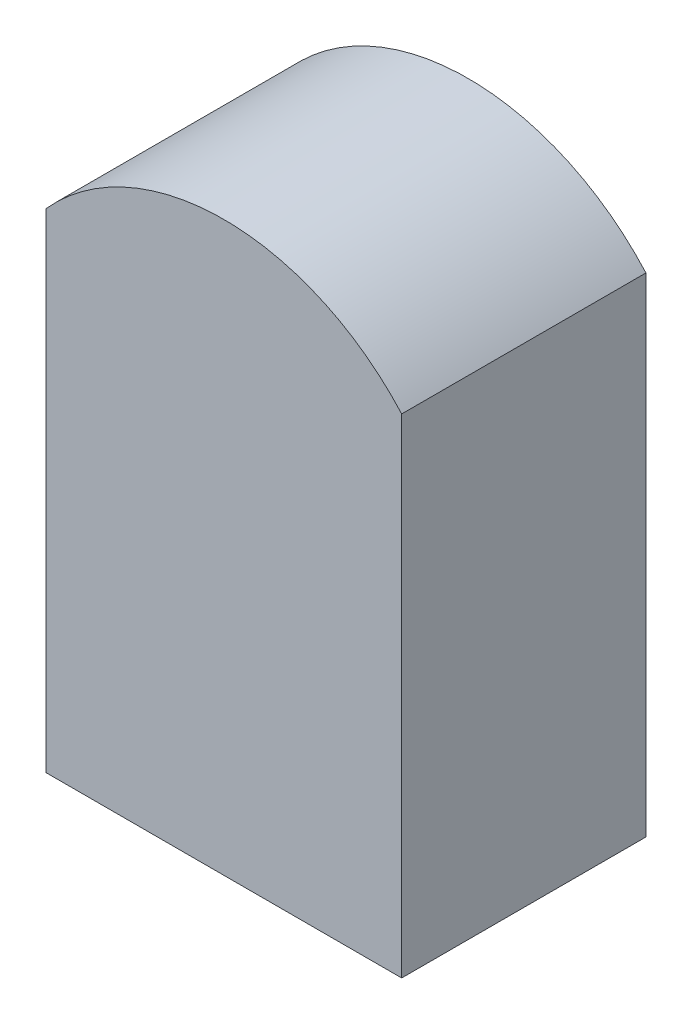
SolidWorks part; units mm, degrees
ref_plane "Front Plane" through (0, 0, 0) normal (0, 0, 1) x (1, 0, 0)
ref_plane "Top Plane" through (0, 0, 0) normal (0, 1, 0) x (1, 0, 0)
ref_plane "Right Plane" through (0, 0, 0) normal (1, 0, 0) x (0, 0, -1)
sketch "Sketch1" plane through (0, 0, 0) normal (0, 0, 1) x (1, 0, 0)
  line L1 (4.268, 6.5) -> (4.293, 6.5)
  line L2 (0.0063, 6.5) -> (0.0063, -0.5)
  line L3 (0.0063, -0.5) -> (5.1022, -0.5)
  line L4 (5.1022, 6.5) -> (5.1022, -0.5)
  arc A0 (0.0063, 6.5) -> (5.1022, 6.5) centre (2.5542, 4.2227) cw
  point P5 (2.5542, 3.952)
  dimension "D1" = 7
extrude "Boss-Extrude2" add sketch "Sketch1" along normal blind 3.5
